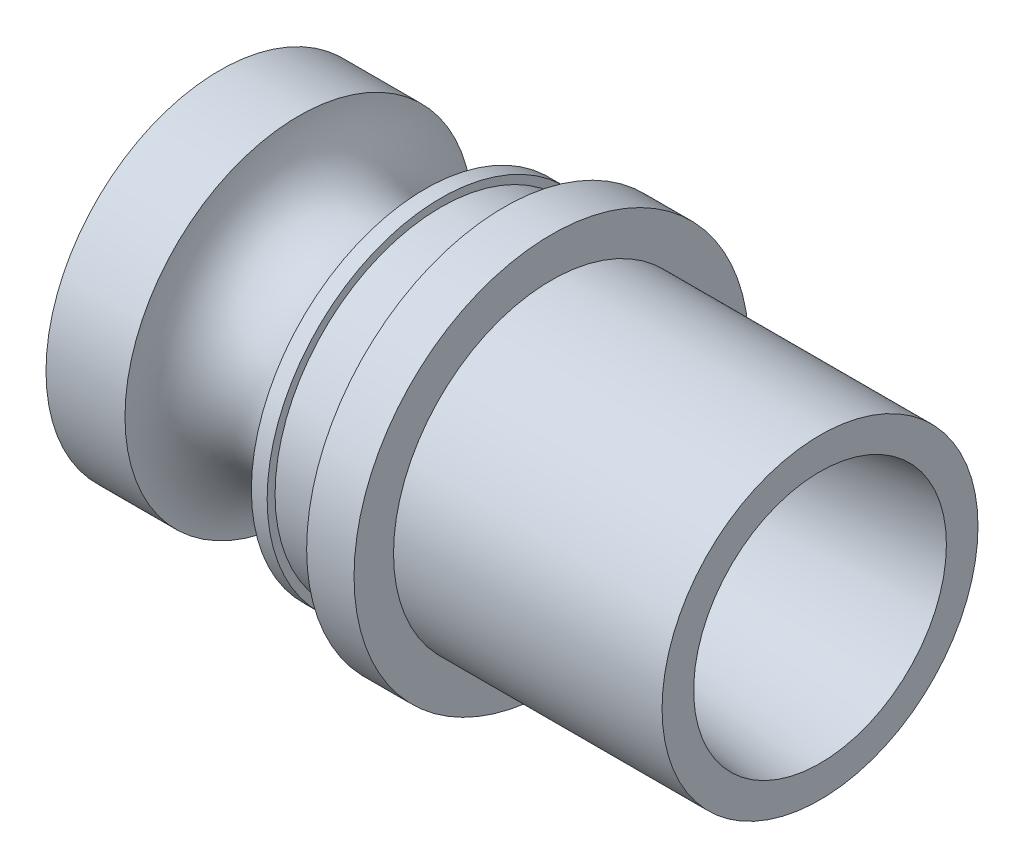
SolidWorks part; units mm, degrees
ref_plane "Спереди" through (0, 0, 0) normal (0, 0, 1) x (1, 0, 0)
ref_plane "Сверху" through (0, 0, 0) normal (0, 1, 0) x (1, 0, 0)
ref_plane "Справа" through (0, 0, 0) normal (1, 0, 0) x (0, 0, -1)
sketch "Эскиз1" plane through (0, 0, 0) normal (0, 0, 1) x (1, 0, 0)
  line L0 (-2.2317, 0) -> (-21.2317, 0)
  line L1 (-21.2317, 0) -> (-21.2317, 5.5)
  line L2 (-21.2317, 5.5) -> (-14.2317, 5.5)
  line L3 (-14.2317, 5.5) -> (-14.2317, 5.25)
  line L4 (-14.2317, 5.25) -> (-12.2317, 5.25)
  line L5 (-12.2317, 5.25) -> (-12.2317, 6.25)
  line L6 (-12.2317, 6.25) -> (-10.7317, 6.25)
  line L7 (-10.7317, 6.25) -> (-10.7317, 5)
  line L8 (-10.7317, 5) -> (-2.2317, 5)
  line L9 (-2.2317, 5) -> (-2.2317, 0)
  dimension "D1" = 19
  dimension "D2" = 5
  dimension "D3" = 6.25
  dimension "D4" = 5.5
  dimension "D5" = 7
  dimension "D6" = 9
  dimension "D7" = 1.5
  dimension "D8" = 5.25
  dimension "D9" = 2.2317
revolve "Повернуть1" add sketch "Эскиз1" angle 360 about L0
sketch "Эскиз2" plane through (0, 0, 0) normal (0, 0, 1) x (1, 0, 0)
  line L0 (-2.2317, 0) -> (-21.2317, 0)
  line L1 (-2.2317, -5) -> (-2.2317, 5) construction
  line L2 (-21.2317, 5.5) -> (-21.2317, -5.5) construction
  line L3 (-21.2317, 0) -> (-21.2317, 5.0393)
  line L4 (-2.2317, 0) -> (-2.2317, 4)
  line L5 (-2.2317, 4) -> (-15.2317, 2.5188)
  line L6 (-15.2317, 2.5188) -> (-15.6088, 2)
  line L7 (-15.6088, 2) -> (-17.2317, 2)
  arc A0 (-21.2317, 5.0393) -> (-17.2317, 2) centre (-21.8473, 0.0773) cw
  circle A1 centre (-16.7317, 5.5) radius 2
  dimension "D5" = 5
  dimension "D10" = 4
  dimension "D1" = 4
  dimension "D2" = 13
  dimension "D3" = 4
  dimension "D4" = 2
  dimension "D6" = 15.6088
  dimension "D7" = 21.8473
  dimension "D8" = 2.5188
  dimension "D9" = 16.7317
  dimension "D11" = 5.5
revolve "Вырез-Повернуть2" cut sketch "Эскиз2" angle 360 about L0
